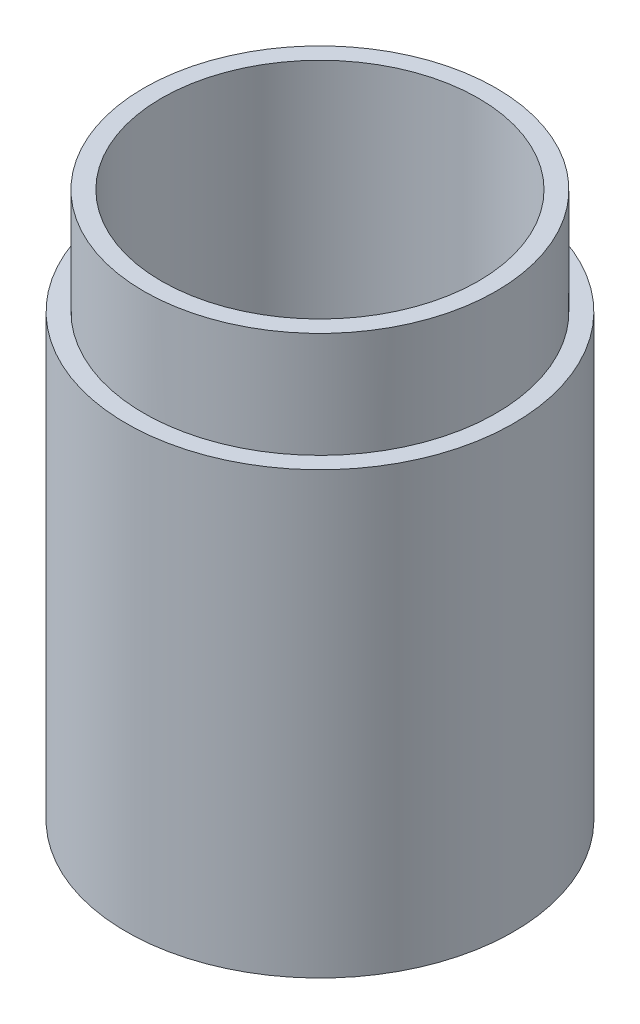
SolidWorks part; units mm, degrees
ref_plane "Front Plane" through (0, 0, 0) normal (0, 0, 1) x (1, 0, 0)
ref_plane "Top Plane" through (0, 0, 0) normal (0, 1, 0) x (1, 0, 0)
ref_plane "Right Plane" through (0, 0, 0) normal (1, 0, 0) x (0, 0, -1)
sketch "Sketch1" plane through (0, 0, 0) normal (0, 1, 0) x (1, 0, 0)
  circle A2 centre (0, 0) radius 45
  dimension "D1" = 90
extrude "Boss-Extrude2" add sketch "Sketch1" along normal blind 150 contours A2
shell "Shell1" thickness 5
sketch "Sketch2" plane through (0, -5, 0) normal (0, -1, 0) x (-1, 0, 0)
  circle A0 centre (0, 0) radius 50
  circle A1 centre (0, 0) radius 55
extrude "Boss-Extrude3" add sketch "Sketch2" against normal blind 125
